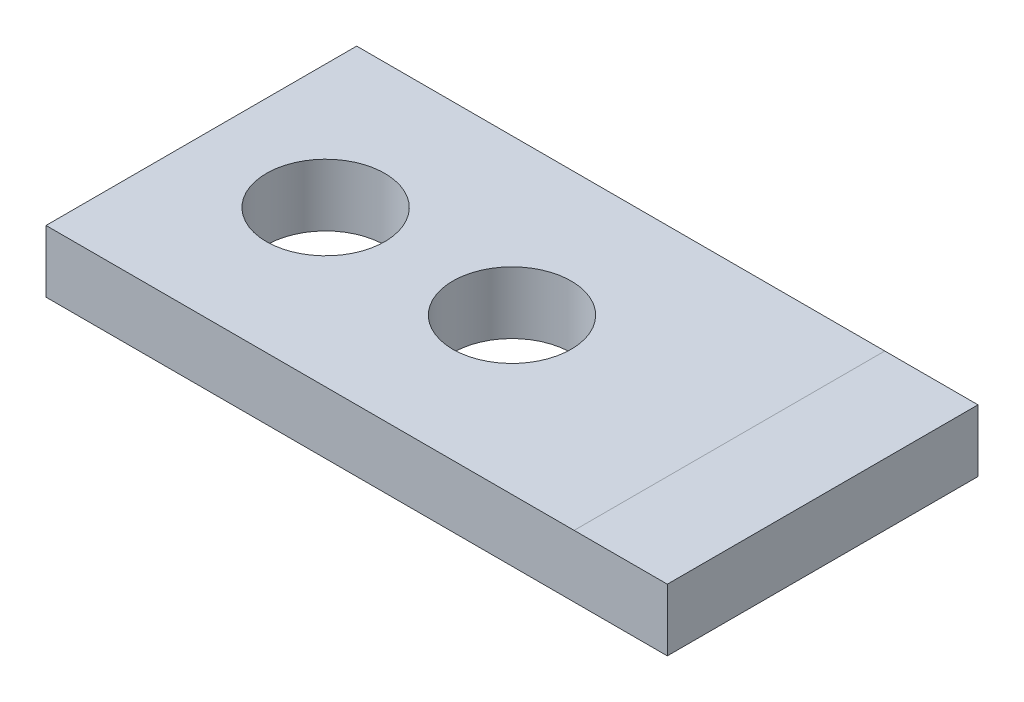
SolidWorks part; units mm, degrees
material "ASTM A36 Steel"
ref_plane "Front Plane" through (0, 0, 0) normal (0, 0, 1) x (1, 0, 0)
ref_plane "Top Plane" through (0, 0, 0) normal (0, 1, 0) x (1, 0, 0)
ref_plane "Right Plane" through (0, 0, 0) normal (1, 0, 0) x (0, 0, -1)
sketch "Sketch1" plane through (0, 0, 0) normal (0, 1, 0) x (1, 0, 0)
  line L1 (0, 0) -> (100, 0)
  line L2 (0, 0) -> (0, 50)
  line L3 (0, 50) -> (100, 50)
  line L4 (100, 0) -> (100, 50)
  circle A0 centre (20, 25) radius 9.525
  circle A1 centre (50, 25) radius 9.525
  point P9 (0, 0)
  point P10 (0, 25)
  point P11 (55.3223, 30.2703)
  point P12 (0, 0)
  point P13 (50, 50)
  dimension "D4" = 19.05
  dimension "D1" = 100
  dimension "D2" = 50
  dimension "D3" = 30
extrude "Boss-Extrude1" add sketch "Sketch1" along normal blind 10
sketch "Sketch2" plane through (0, 10, 0) normal (0, 1, 0) x (1, 0, 0)
  line L0 (0, 0) -> (100, 0) construction
  line L1 (100, 50) -> (85, 50)
  line L2 (100, 50) -> (100, 0)
  line L3 (100, 0) -> (85, 0)
  line L4 (85, 50) -> (85, 0)
  dimension "D1" = 15
split line "Split Line1"
sketch "Sketch3" plane through (0, 0, 0) normal (0, -1, 0) x (1, 0, 0)
  line L0 (100, -50) -> (0, -50) construction
  line L1 (0, 0) -> (35, 0)
  line L2 (0, 0) -> (0, -50)
  line L3 (0, -50) -> (35, -50)
  line L4 (35, 0) -> (35, -50)
  dimension "D1" = 35
split line "Split Line2"
